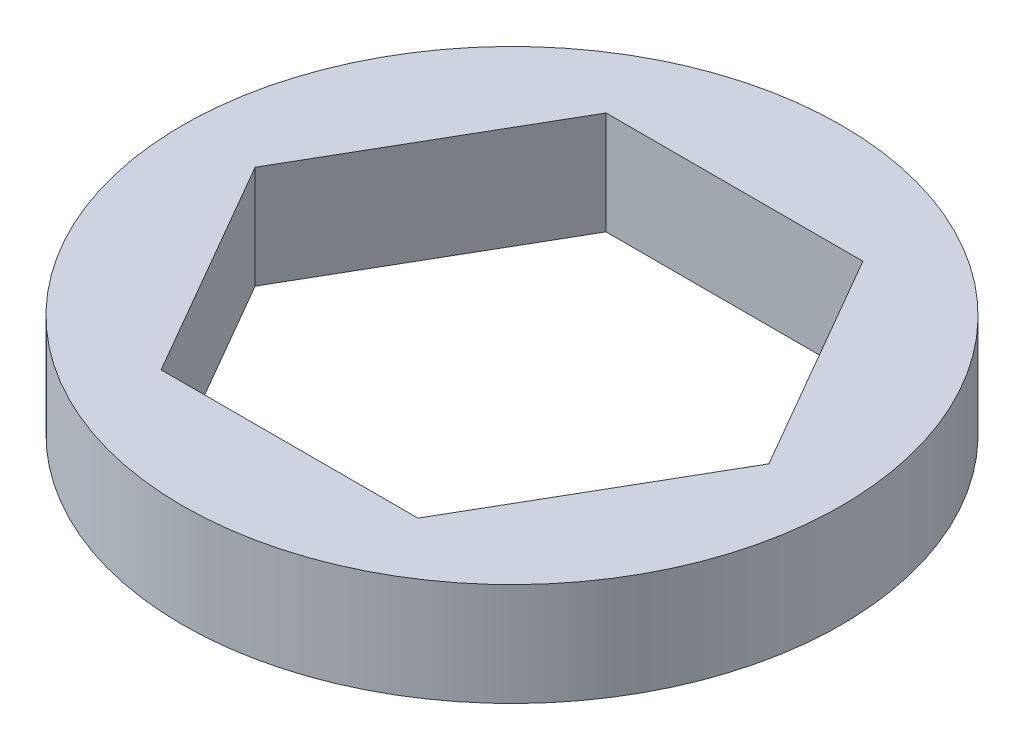
SolidWorks part; units mm, degrees
ref_plane "Front Plane" through (0, 0, 0) normal (0, 0, 1) x (1, 0, 0)
ref_plane "Top Plane" through (0, 0, 0) normal (0, 1, 0) x (1, 0, 0)
ref_plane "Right Plane" through (0, 0, 0) normal (1, 0, 0) x (0, 0, -1)
sketch "Sketch1" plane through (0, 0, 0) normal (0, 1, 0) x (1, 0, 0)
  line L1 (7.9189, 0) -> (3.9595, 6.858)
  line L2 (3.9595, 6.858) -> (-3.9595, 6.858)
  line L3 (-3.9595, 6.858) -> (-7.9189, 0)
  line L4 (-7.9189, 0) -> (-3.9595, -6.858)
  line L5 (-3.9595, -6.858) -> (3.9595, -6.858)
  line L6 (3.9595, -6.858) -> (7.9189, 0)
  circle A0 centre (0, 0) radius 6.858 construction
  circle A1 centre (0, 0) radius 10.16
  dimension "D2" = 20.32
  dimension "D1" = 13.716
extrude "Boss-Extrude1" add sketch "Sketch1" along normal blind 3.175
